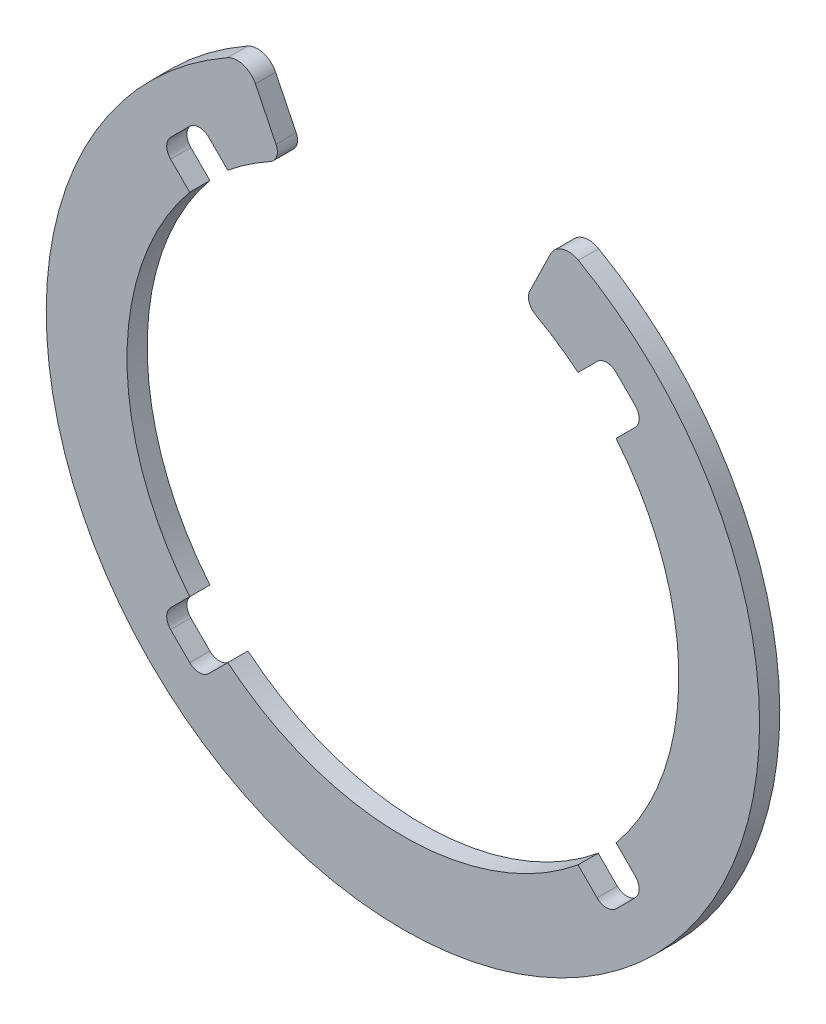
SolidWorks part; units mm, degrees
ref_plane "Plan de face" through (0, 0, 0) normal (0, 0, 1) x (1, 0, 0)
ref_plane "Plan de dessus" through (0, 0, 0) normal (0, 1, 0) x (1, 0, 0)
ref_plane "Plan de droite" through (0, 0, 0) normal (1, 0, 0) x (0, 0, -1)
sketch "Esquisse1" plane through (0, 0, 0) normal (0, 0, 1) x (1, 0, 0)
  circle A0 centre (0, 0) radius 41
  circle A1 centre (0, 0) radius 53
  dimension "D1" = 12
  dimension "D2" = 82
extrude "Boss.-Extru.1" add sketch "Esquisse1" along normal blind 3
sketch "Esquisse2" plane through (0, 0, 3) normal (0, 0, 1) x (1, 0, 0)
  line L0 (0, 0) -> (0, 54) construction
  line L1 (0, 0) -> (-18, 36.8375) construction
  line L2 (-18, 36.8375) -> (-23.2683, 47.6192)
  line L3 (18, 36.8375) -> (23.2683, 47.6192)
  circle A0 centre (0, 0) radius 53 construction
  arc A1 (-23.2683, 47.6192) -> (23.2683, 47.6192) centre (0, 0) cw
  arc A2 (-18, 36.8375) -> (18, 36.8375) centre (0, 0) cw
  circle A3 centre (0, 0) radius 41 construction
  dimension "D1" = 36
extrude "Enlèv. mat.-Extru.1" cut sketch "Esquisse2" against normal through all both and the other way through all
sketch "Esquisse3" plane through (0, 0, 3) normal (0, 0, 1) x (1, 0, 0)
  line L0 (0, 0) -> (53, 0) construction
  line L1 (0, 0) -> (0, -53) construction
  line L2 (0, 0) -> (37.4767, -37.4767) construction
  line L3 (26.0246, -31.6815) -> (31.6815, -26.0246)
  line L4 (31.6815, -26.0246) -> (35.9241, -30.2673)
  line L5 (35.9241, -30.2673) -> (30.2673, -35.9241)
  line L6 (26.0246, -31.6815) -> (30.2673, -35.9241)
  line L7 (-26.0246, -31.6815) -> (-30.2673, -35.9241)
  line L8 (-35.9241, -30.2673) -> (-30.2673, -35.9241)
  line L9 (-31.6815, -26.0246) -> (-35.9241, -30.2673)
  line L10 (-26.0246, -31.6815) -> (-31.6815, -26.0246)
  line L11 (-26.0246, 31.6815) -> (-31.6815, 26.0246)
  line L12 (-31.6815, 26.0246) -> (-35.9241, 30.2673)
  line L13 (-35.9241, 30.2673) -> (-30.2673, 35.9241)
  line L14 (-26.0246, 31.6815) -> (-30.2673, 35.9241)
  line L15 (26.0246, 31.6815) -> (30.2673, 35.9241)
  line L16 (35.9241, 30.2673) -> (30.2673, 35.9241)
  line L17 (31.6815, 26.0246) -> (35.9241, 30.2673)
  line L18 (26.0246, 31.6815) -> (31.6815, 26.0246)
  arc A0 (-23.2683, 47.6192) -> (23.2683, 47.6192) centre (0, 0) ccw construction
  arc A2 (-18, 36.8375) -> (18, 36.8375) centre (0, 0) ccw construction
  point P13 (33.0957, -33.0957)
  point P14 (28.8531, -28.8531)
  point P22 (-28.8531, -28.8531)
  point P23 (-33.0957, -33.0957)
  point P32 (-33.0957, 33.0957)
  point P33 (-28.8531, 28.8531)
  point P34 (28.8531, 28.8531)
  point P35 (33.0957, 33.0957)
  dimension "D1" = 45
  dimension "D2" = 8
  dimension "D3" = 6
extrude "Enlèv. mat.-Extru.2" cut sketch "Esquisse3" against normal through all both and the other way through all
fillet "Congé1" radius 3 2 edges at (23.2683, 47.6192, 1.5) (-23.2683, 47.6192, 1.5)
fillet "Congé2" radius 2 10 edges at (30.2673, -35.9241, 1.5) (35.9241, -30.2673, 1.5) (-30.2673, -35.9241, 1.5) (-35.9241, -30.2673, 1.5) (-35.9241, 30.2673, 1.5) (-30.2673, 35.9241, 1.5) (35.9241, 30.2673, 1.5) (30.2673, 35.9241, 1.5) (18, 36.8375, 1.5) (-18, 36.8375, 1.5)
